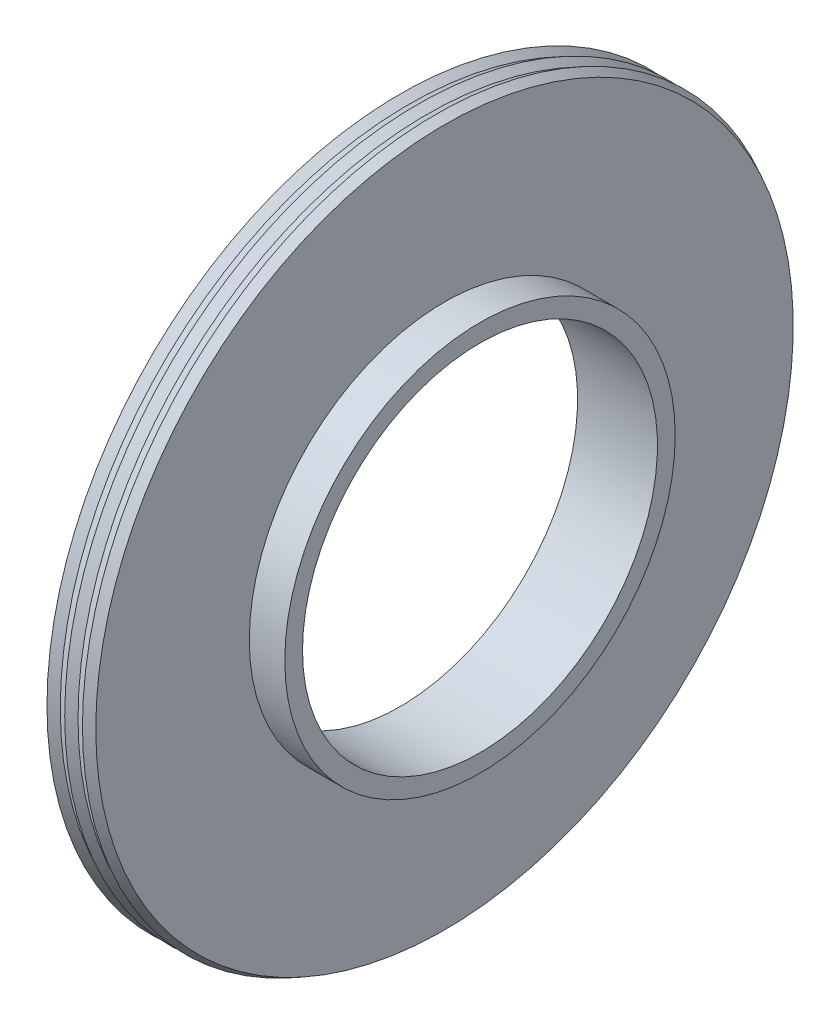
SolidWorks part; units mm, degrees
ref_plane "前视基准面" through (0, 0, 0) normal (0, 0, 1) x (1, 0, 0)
ref_plane "上视基准面" through (0, 0, 0) normal (0, 1, 0) x (1, 0, 0)
ref_plane "右视基准面" through (0, 0, 0) normal (1, 0, 0) x (0, 0, -1)
other "Configuration Table"
sketch "草图1" plane through (0, 0, 0) normal (0, 0, 1) x (1, 0, 0)
  line L0 (-51.8776, 0) -> (77.6777, 0) construction
  line L1 (0, 0) -> (0, 20)
  line L2 (0, 20) -> (9, 20)
  line L3 (9, 20) -> (9, 22)
  line L4 (9, 22) -> (0, 22)
  line L5 (0, 22) -> (0, 20)
  line L6 (0, 0) -> (0, 39.8)
  line L7 (0, 39.8) -> (5, 39.8)
  line L8 (5, 39.8) -> (5, 22)
  line L10 (0, 39.8) -> (1, 39.3)
  line L11 (1, 39.3) -> (2, 39.8)
  line L12 (2, 39.8) -> (3, 39.3)
  line L13 (3, 39.3) -> (4, 39.8)
  line L14 (4, 39.8) -> (5, 39.3)
  line L16 (5, 39.3) -> (6, 39.8) [skipped]
  dimension "D1" = 9
  dimension "D2" = 20
  dimension "D3" = 2
  dimension "D4" = 39.8
  dimension "D5" = 5
  dimension "D8" = 1
  dimension "D9" = 3
revolve "旋转1" add sketch "草图1" angle 360 about L0
